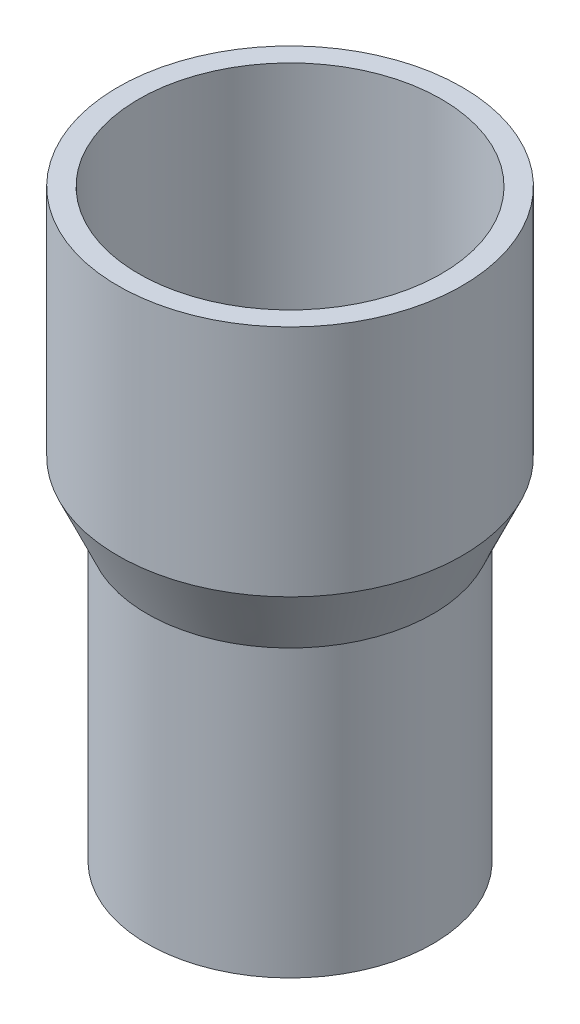
SolidWorks part; units mm, degrees
ref_plane "Front Plane" through (0, 0, 0) normal (0, 0, 1) x (1, 0, 0)
ref_plane "Top Plane" through (0, 0, 0) normal (0, 1, 0) x (1, 0, 0)
ref_plane "Right Plane" through (0, 0, 0) normal (1, 0, 0) x (0, 0, -1)
sketch "Sketch1" plane through (0, 0, 0) normal (0, 0, 1) x (1, 0, 0)
  line L0 (0, 0) -> (0, 45) construction
  line L1 (0, 0) -> (-9.4, 0)
  line L2 (-9.4, 0) -> (-11, 0)
  line L3 (-11, 0) -> (-11, 22)
  line L4 (-11, 22) -> (-13.25, 27)
  line L5 (-13.25, 27) -> (-13.25, 45)
  line L9 (-9.4, 22.3434) -> (-9.4, 0)
  line L10 (-13.25, 45) -> (-11.65, 45)
  line L11 (-11.65, 45) -> (-11.65, 27.3434)
  line L12 (0, 45) -> (-11.65, 45) construction
  line L13 (-11.65, 27.3434) -> (-9.4, 22.3434)
  dimension "D1" = 45
  dimension "D3" = 1.6
  dimension "D4" = 13.25
  dimension "D5" = 22
  dimension "D6" = 18
  dimension "D7" = 1.6
  dimension "D2" = 11
revolve "Revolve1" add sketch "Sketch1" angle 360 about L0
equation "\"D7@Sketch1\"=\"D3@Sketch1\""
